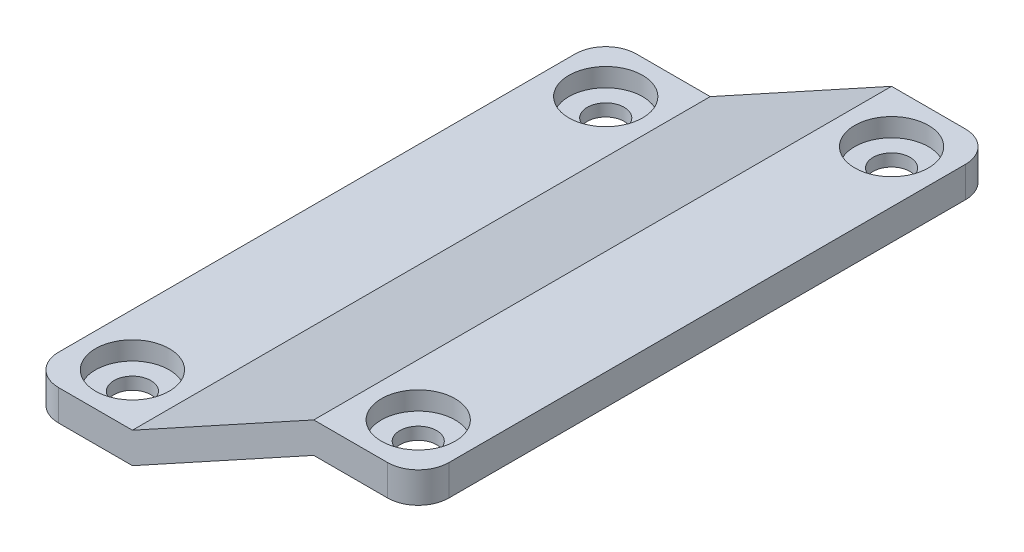
SolidWorks part; units mm, degrees
ref_plane "Front Plane" through (0, 0, 0) normal (0, 0, 1) x (1, 0, 0)
ref_plane "Top Plane" through (0, 0, 0) normal (0, 1, 0) x (1, 0, 0)
ref_plane "Right Plane" through (0, 0, 0) normal (1, 0, 0) x (0, 0, -1)
sketch "Sketch1" plane through (0, 0, 0) normal (0, 0, 1) x (1, 0, 0)
  line L0 (-15.0078, -4.569) -> (14.4922, 11.631)
  line L1 (-15.0078, -9.569) -> (-32.0078, -9.569)
  line L2 (-15.0078, -4.569) -> (-32.0078, -4.569)
  line L3 (-32.0078, -9.569) -> (-32.0078, -4.569)
  line L4 (14.4922, 6.631) -> (31.4922, 6.631)
  line L5 (14.4922, 11.631) -> (31.4922, 11.631)
  line L6 (31.4922, 6.631) -> (31.4922, 11.631)
  line L7 (-15.0078, -9.569) -> (14.4922, 6.631)
extrude "Cover Body" add sketch "Sketch1" against normal blind 94
sketch "Screw Hole outlines" plane through (0, -4.569, 0) normal (0, 1, 0) x (1, 0, 0)
  line L0 (14.4922, 94) -> (-15.0078, 94) construction
  line L1 (-23.5078, 85.5) -> (22.9922, 85.5) construction
  line L2 (-23.5078, 85.5) -> (-23.5078, 8.5) construction
  line L3 (-23.5078, 8.5) -> (22.9922, 8.5) construction
  line L4 (22.9922, 85.5) -> (22.9922, 8.5) construction
  line L6 (31.4922, 94) -> (31.4922, 0) construction
  dimension "D1" = 8.5
  dimension "D2" = 8.5
hole_wizard "CBORE for M6 Hex Head Bolt1" positions "Sketch2" profile "Sketch4" counterbore size "M6" standard "ANSI Metric" end condition through all
sketch "Sketch2" plane through (0, -4.569, 0) normal (0, 1, 0) x (1, 0, 0)
  point P0 (-23.5078, 85.5)
  point P3 (-23.5078, 8.5)
sketch "Sketch4" plane through (-23.5078, -4.569, -85.5) normal (1, 0, 0) x (0, 0, 1)
  line L0 (0, 0) -> (0, 5)
  line L1 (0, 5) -> (3, 5)
  line L3 (3, 5) -> (3, 3)
  line L4 (3, 3) -> (6, 3)
  line L5 (6, 3) -> (6, 0)
  line L7 (6, 0) -> (0, 0)
  line L11 (0, -6.35) -> (0, 107.95) construction
  dimension "Thru Hole Dia." = 6
  dimension "Thru Hole Depth" = 5
  dimension "C'Bore Dia." = 12
  dimension "C'Bore Depth" = 3
ref_plane "Upper Lid Plane" through (22.9922, 0, 0) normal (1, 0, 0) x (0, 0, -1)
sketch "Sketch9" plane through (22.9922, 0, 0) normal (1, 0, 0) x (0, 0, -1)
  line L0 (8.5, -4.569) -> (8.5, 11.631) construction
  line L1 (85.5, -4.569) -> (8.5, -4.569) construction
  line L2 (85.5, -4.569) -> (8.5, -4.569) construction
  line L3 (94, 11.631) -> (0, 11.631) construction
  line L4 (85.5, -4.569) -> (85.5, 11.631) construction
hole_wizard "CBORE for M6 Hex Head Bolt2" positions "Sketch10" profile "Sketch11" counterbore size "M6" standard "ANSI Metric" end condition up to next
sketch "Sketch10" plane through (0, 11.631, 0) normal (0, 1, 0) x (1, 0, 0)
  point P0 (22.9922, 8.5)
  point P3 (22.9922, 85.5)
sketch "Sketch11" plane through (22.9922, 11.631, -8.5) normal (1, 0, 0) x (0, 0, 1)
  line L0 (0, 0) -> (0, 5)
  line L1 (0, 5) -> (3, 5)
  line L3 (3, 5) -> (3, 3)
  line L4 (3, 3) -> (6, 3)
  line L5 (6, 3) -> (6, 0)
  line L7 (6, 0) -> (0, 0)
  line L11 (0, -6.35) -> (0, 107.95) construction
  dimension "Thru Hole Dia." = 6
  dimension "Thru Hole Depth" = 5
  dimension "C'Bore Dia." = 12
  dimension "C'Bore Depth" = 3
fillet "Fillet1" radius 5 4 edges at (-32.0078, -7.069, -94) (31.4922, 9.131, -94) (31.4922, 9.131, 0) (-32.0078, -7.069, 0)
